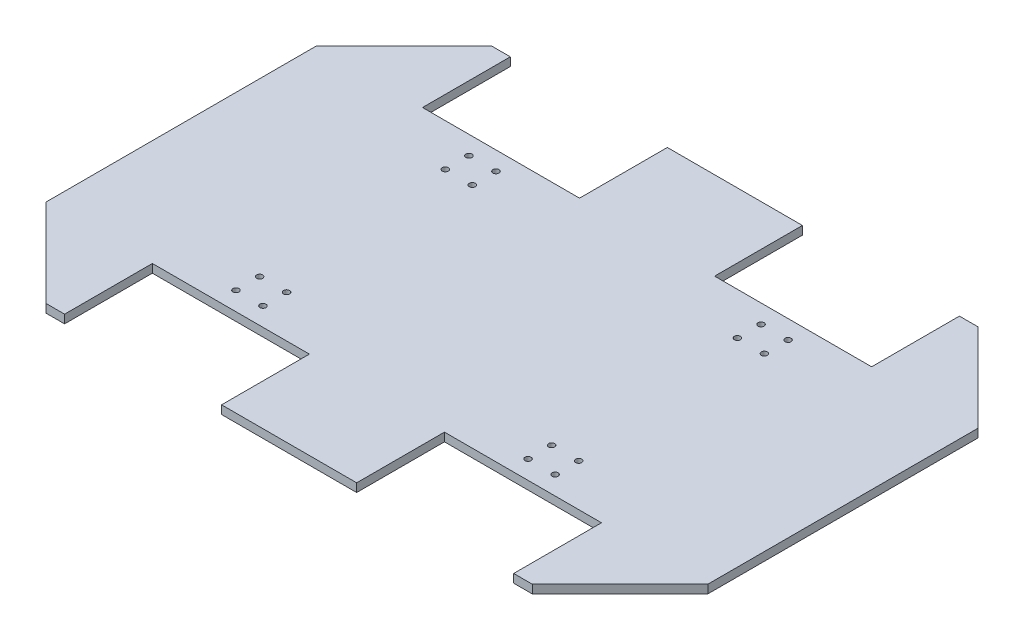
SolidWorks part; units mm, degrees
ref_plane "Front Plane" through (0, 0, 0) normal (0, 0, 1) x (1, 0, 0)
ref_plane "Top Plane" through (0, 0, 0) normal (0, 1, 0) x (1, 0, 0)
ref_plane "Right Plane" through (0, 0, 0) normal (1, 0, 0) x (0, 0, -1)
sketch "Sketch1" plane through (0, 0, 0) normal (0, 1, 0) x (1, 0, 0)
  line L0 (-196, 0) -> (196, 0) construction
  line L1 (196, -80) -> (196, 80)
  line L2 (196, 80) -> (144, 132)
  line L3 (144, 132) -> (133, 132)
  line L4 (133, 132) -> (133, 80)
  line L5 (133, 80) -> (40, 80)
  line L6 (40, 80) -> (40, 132)
  line L7 (40, 132) -> (-40, 132)
  line L8 (0, 0) -> (0, 132) construction
  line L9 (144, -132) -> (144, -80) construction
  line L10 (144, -80) -> (196, -80) construction
  line L11 (40, -132) -> (-40, -132)
  line L12 (40, -80) -> (40, -132)
  line L13 (133, -80) -> (40, -80)
  line L14 (133, -132) -> (133, -80)
  line L15 (144, -132) -> (133, -132)
  line L16 (196, -80) -> (144, -132)
  line L17 (86.5, -80) -> (86.5, -69) construction
  line L18 (86.5, -69) -> (94.5, -69) construction
  line L19 (-196, -80) -> (-144, -132)
  line L20 (-144, -132) -> (-133, -132)
  line L21 (-133, -132) -> (-133, -80)
  line L22 (-133, -80) -> (-40, -80)
  line L23 (-40, -80) -> (-40, -132)
  line L24 (-40, 80) -> (-40, 132)
  line L25 (-133, 80) -> (-40, 80)
  line L26 (-133, 132) -> (-133, 80)
  line L27 (-144, 132) -> (-133, 132)
  line L28 (-196, 80) -> (-144, 132)
  line L29 (-196, -80) -> (-196, 80)
  line L30 (94.5, -69) -> (94.5, -62) construction
  line L31 (94.5, -62) -> (86.5, -62) construction
  line L32 (86.5, -62) -> (86.5, -69) construction
  circle A0 centre (94.5, -69) radius 1.8
  circle A1 centre (94.5, -55) radius 1.8
  circle A2 centre (78.5, -69) radius 1.8
  circle A3 centre (78.5, -55) radius 1.8
  circle A4 centre (94.5, 69) radius 1.8
  circle A5 centre (78.5, 69) radius 1.8
  circle A6 centre (78.5, 55) radius 1.8
  circle A7 centre (94.5, 55) radius 1.8
  circle A8 centre (-94.5, -69) radius 1.8
  circle A9 centre (-94.5, -55) radius 1.8
  circle A10 centre (-78.5, -55) radius 1.8
  circle A11 centre (-78.5, -69) radius 1.8
  circle A12 centre (-78.5, 55) radius 1.8
  circle A13 centre (-78.5, 69) radius 1.8
  circle A14 centre (-94.5, 55) radius 1.8
  circle A15 centre (-94.5, 69) radius 1.8
  point P29 (0, -132)
  dimension "D14" = 3.6
  dimension "D1" = 196
  dimension "D2" = 80
  dimension "D3" = 40
  dimension "D4" = 52
  dimension "D5" = 93
  dimension "D6" = 52
  dimension "D7" = 52
  dimension "D8" = 52
  dimension "D9" = 80
  dimension "D10" = 160
  dimension "D11" = 11
  dimension "D12" = 8
  dimension "D13" = 7
extrude "Boss-Extrude1" add sketch "Sketch1" along normal blind 5
